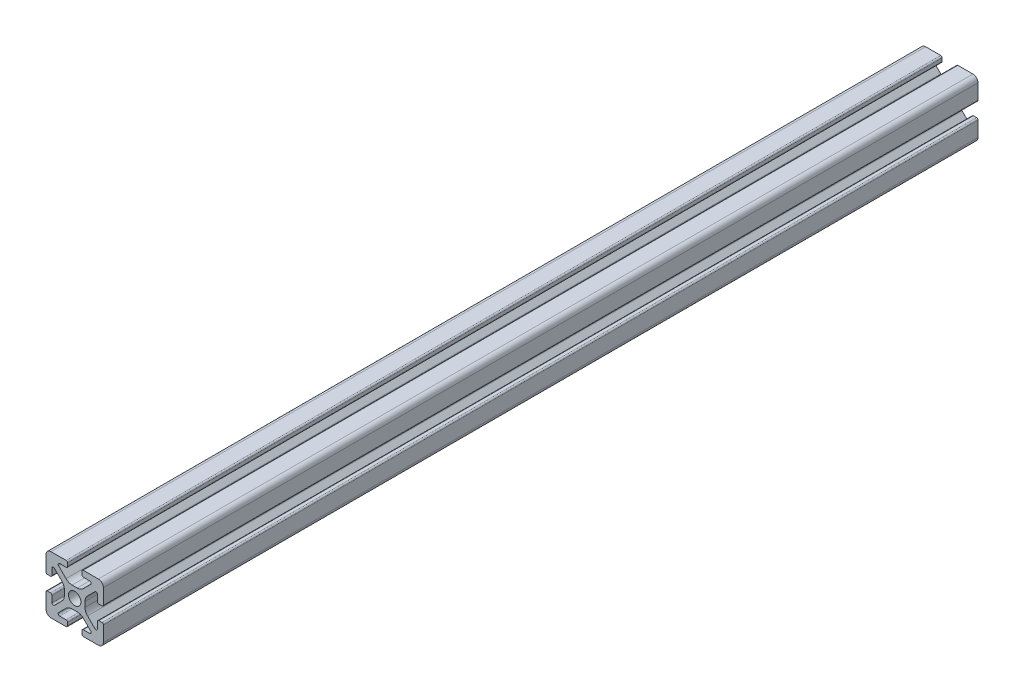
SolidWorks part; units mm, degrees
material "6061 Alloy"
ref_plane "Front Plane" through (0, 0, 0) normal (0, 0, 1) x (1, 0, 0)
ref_plane "Top Plane" through (0, 0, 0) normal (0, 1, 0) x (1, 0, 0)
ref_plane "Right Plane" through (0, 0, 0) normal (1, 0, 0) x (0, 0, -1)
sketch "Sketch2" plane through (0, 0, 0) normal (0, 0, 1) x (1, 0, 0)
  line L0 (0, 10) -> (0, -10) construction
  line L1 (-10, 0) -> (10, 0) construction
  line L2 (2.5, -10) -> (10, -10)
  line L3 (10, -10) -> (10, -2.5)
  line L4 (2.5, -10) -> (2.5, -7.9246)
  line L5 (2.5, -7.9246) -> (6.4571, -7.9246)
  line L6 (6.4571, -7.9246) -> (2.1325, -3.6)
  line L7 (0, 0) -> (10, -10) construction
  line L8 (10, -2.5) -> (7.9246, -2.5)
  line L9 (7.9246, -2.5) -> (7.9246, -6.4571)
  line L10 (7.9246, -6.4571) -> (3.6, -2.1325)
  line L11 (5.7623, -4.2948) -> (4.2948, -5.7623) construction
  circle A0 centre (0, 0) radius 2.15
  arc A1 (5.25, -7.9246) -> (5.6036, -7.0711) centre (5.25, -7.4246) ccw construction
  point P8 (0, -3.6)
  point P16 (5.0286, -5.0286)
  dimension "Center Hole Diameter" = 4.3
  dimension "D3" = 0.5
  dimension "Rail Height" = 20
  dimension "Rail Width" = 20
  dimension "T-Slot Width" = 5
  dimension "Slot Depth" = 6.4
  dimension "Slot Inner Width" = 11.5
sketch "Sketch3" plane through (0, 0, 0) normal (1, 0, 0) x (0, 0, -1)
  line L0 (-1524, -10) -> (1524, -10) construction
  line L1 (-1498.6, 0) -> (1498.6, 0) construction
  line L2 (0, 10) -> (0, -10) construction
  line L3 (0, 10) -> (0, -10) construction
  point P6 (-1498.6, 0)
  point P8 (1498.6, 0)
  dimension "Length" = 3048
  dimension "D1" = 25.4
sketch "Sketch4" plane through (0, 0, 0) normal (0, 0, 1) x (1, 0, 0)
  line L0 (3, -10) -> (8.25, -10)
  line L1 (2.5, -10) -> (10, -10) construction
  line L2 (2.5, -10) -> (2.5, -7.9246) construction
  line L3 (2.5, -7.9246) -> (6.4571, -7.9246) construction
  line L4 (2.5, -8.4246) -> (2.5, -9.5)
  line L5 (3, -7.9246) -> (5.25, -7.9246)
  line L6 (0, -3.6) -> (0.8898, -3.6)
  line L7 (6.4571, -7.9246) -> (2.1325, -3.6) construction
  line L8 (3.0112, -4.4787) -> (5.6036, -7.0711)
  line L9 (10, -10) -> (10, -2.5) construction
  line L10 (7.9246, -6.4571) -> (3.6, -2.1325) construction
  line L11 (7.9246, -2.5) -> (7.9246, -6.4571) construction
  line L12 (7.9246, -5.25) -> (7.9246, -3)
  line L13 (10, -2.5) -> (7.9246, -2.5) construction
  line L14 (8.4246, -2.5) -> (9.5, -2.5)
  line L15 (10, -3) -> (10, -8.25)
  line L16 (7.0711, -5.6036) -> (4.4787, -3.0112)
  line L17 (3.6, 0) -> (3.6, -0.8898)
  line L18 (-10, 0) -> (10, 0) construction
  line L19 (0, -3.6) -> (0, -2.15)
  line L20 (0, 10) -> (0, -10) construction
  line L21 (3.6, 0) -> (2.15, 0)
  arc A0 (2.5, -9.5) -> (3, -10) centre (3, -9.5) ccw
  arc A1 (5.25, -7.9246) -> (5.6036, -7.0711) centre (5.25, -7.4246) ccw construction
  arc A2 (2.5, -8.4246) -> (3, -7.9246) centre (3, -8.4246) cw
  arc A3 (5.25, -7.9246) -> (5.6036, -7.0711) centre (5.25, -7.4246) ccw
  arc A4 (0.8898, -3.6) -> (3.0112, -4.4787) centre (0.8898, -6.6) cw
  arc A5 (8.25, -10) -> (10, -8.25) centre (8.25, -8.25) ccw
  arc A6 (7.0711, -5.6036) -> (7.9246, -5.25) centre (7.4246, -5.25) ccw
  arc A7 (7.9246, -3) -> (8.4246, -2.5) centre (8.4246, -3) cw
  arc A8 (9.5, -2.5) -> (10, -3) centre (9.5, -3) cw
  arc A9 (4.4787, -3.0112) -> (3.6, -0.8898) centre (6.6, -0.8898) cw
  circle A10 centre (0, 0) radius 2.15 construction
  arc A11 (0, -2.15) -> (2.15, 0) centre (0, 0) ccw
  dimension "D1" = 1.75
  dimension "D2" = 3
extrude "Boss-Extrude1" add sketch "Sketch4" along normal mid plane 3048
mirror "Mirror1" about plane through (0, 0, 0) normal (1, 0, 0) of bodies 134
mirror "Mirror2" about plane through (0, 0, 0) normal (0, 1, 0) of bodies 135
sketch "Sketch5" plane through (0, 10, 0) normal (0, 1, 0) x (1, 0, 0)
  line L0 (10, -1524) -> (10, 1524) construction
  line L1 (-10, -1524) -> (10, -1524)
  line L2 (-10, -1524) -> (-10, 1219.2)
  line L3 (-10, 1219.2) -> (10, 1219.2)
  line L4 (10, -1524) -> (10, 1219.2)
  line L5 (3, 1524) -> (8.25, 1524) construction
  dimension "D1" = 304.8
extrude "Cut-Extrude1" cut sketch "Sketch5" against normal through all
equation "\"D3@Sketch2\"=\"T-Slot Width@Sketch2\"*0.1"
equation "\"D1@Sketch4\"=\"D3@Sketch2\"*3.5"
equation "\"D2@Sketch4\"=\"D3@Sketch2\"*6"
equation "\"D1@Boss-Extrude1\"=\"Length@Sketch3\""
